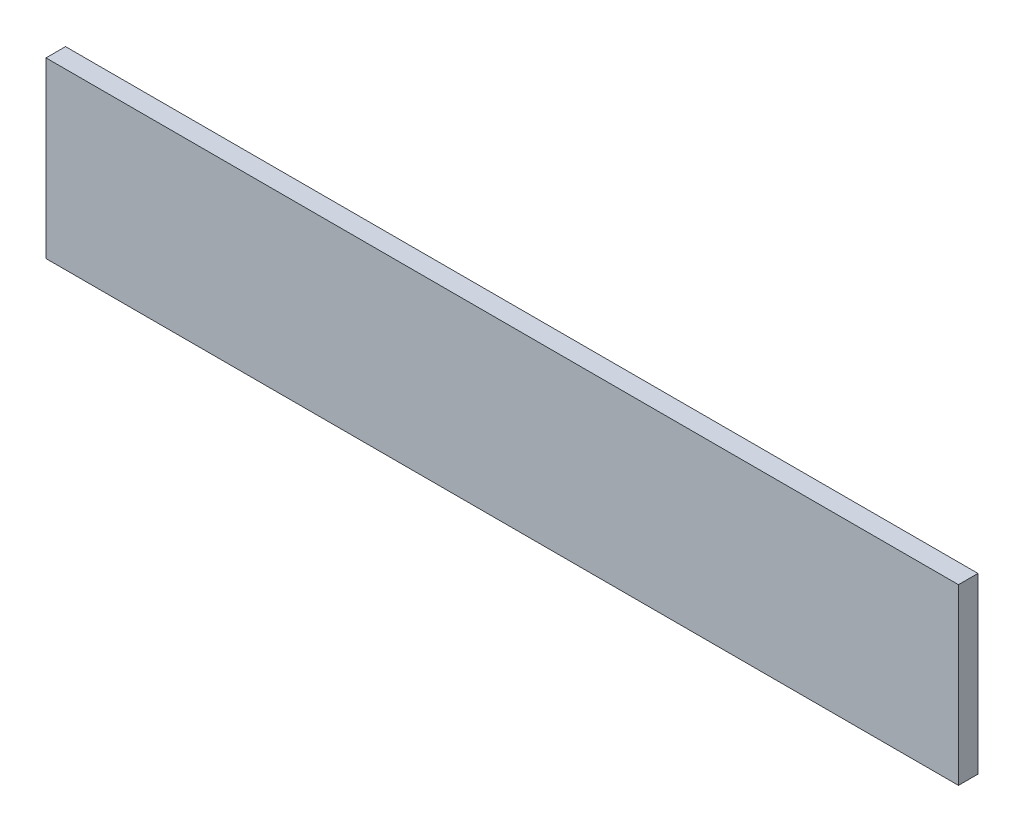
SolidWorks part; units mm, degrees
material "Custom Plastic"
ref_plane "X-Y Datum" through (0, 0, 0) normal (0, 0, 1) x (1, 0, 0)
ref_plane "X-Z Datum" through (0, 0, 0) normal (0, 1, 0) x (1, 0, 0)
ref_plane "Y-Z Datum" through (0, 0, 0) normal (1, 0, 0) x (0, 0, -1)
sketch "Sketch1" plane through (0, 0, 0) normal (0, 0, 1) x (1, 0, 0)
  line L1 (-148.415, -28.275) -> (148.415, -28.275)
  line L2 (-148.415, -28.275) -> (-148.415, 28.275)
  line L3 (-148.415, 28.275) -> (148.415, 28.275)
  line L4 (148.415, -28.275) -> (148.415, 28.275)
  line L5 (-148.415, -28.275) -> (148.415, 28.275) construction
  line L6 (-148.415, 28.275) -> (148.415, -28.275) construction
  point P0 (0, 0)
extrude "Boss-Extrude1" add sketch "Sketch1" along normal blind 6.35
